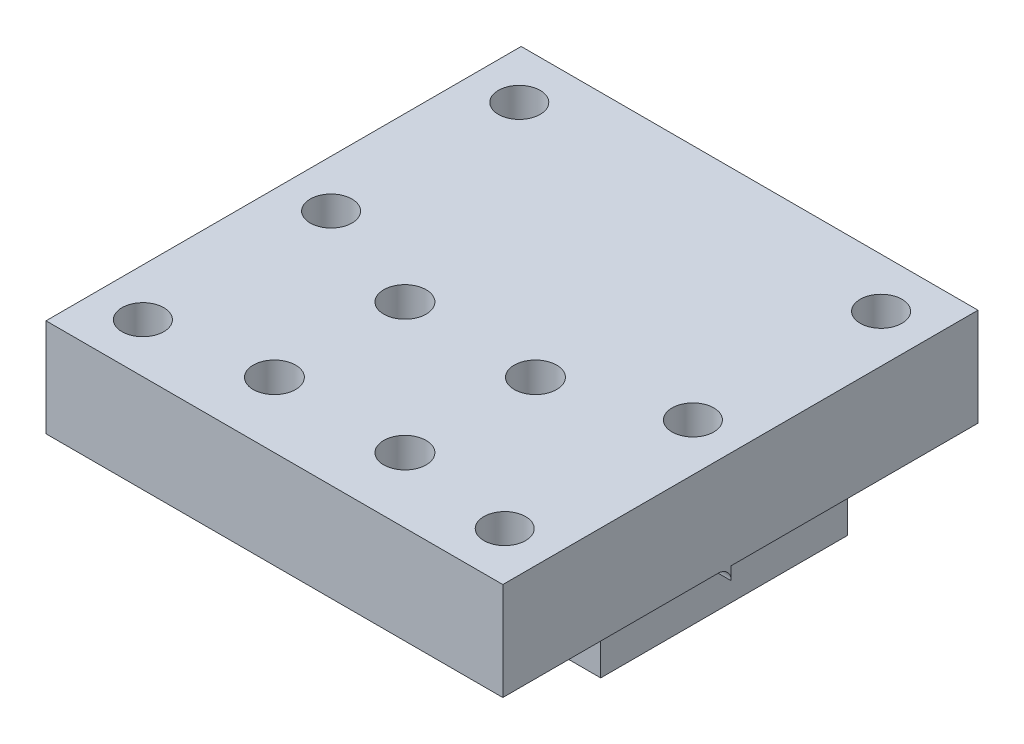
SolidWorks part; units mm, degrees
ref_plane "Front Plane" through (0, 0, 0) normal (0, 0, 1) x (1, 0, 0)
ref_plane "Top Plane" through (0, 0, 0) normal (0, 1, 0) x (1, 0, 0)
ref_plane "Right Plane" through (0, 0, 0) normal (1, 0, 0) x (0, 0, -1)
sketch "Sketch1" plane through (0, 0, 0) normal (0, 1, 0) x (1, 0, 0)
  line L1 (-35, 20) -> (35, 20)
  line L2 (-35, 20) -> (-35, -20)
  line L3 (-35, -20) -> (35, -20)
  line L4 (35, 20) -> (35, -20)
  line L5 (-35, 20) -> (35, -20) construction
  line L6 (-35, -20) -> (35, 20) construction
  line L7 (-10, 10) -> (10, 10) construction
  line L8 (-10, 10) -> (-10, -10) construction
  line L9 (-10, -10) -> (10, -10) construction
  line L10 (10, 10) -> (10, -10) construction
  line L11 (-10, 10) -> (10, -10) construction
  line L12 (-10, -10) -> (10, 10) construction
  circle A0 centre (10, 10) radius 1.6
  circle A1 centre (10, -10) radius 1.6
  circle A2 centre (-10, -10) radius 1.6
  circle A3 centre (-10, 10) radius 1.6
  point P0 (0, 0)
  point P5 (0, 0)
  point P12 (-10, 9.9651)
  point P21 (0, 0)
  dimension "D3" = 3.2
  dimension "D1" = 20
  dimension "D2" = 20
  dimension "D5" = 70
  dimension "D6" = 40
  dimension "D4" = 4
extrude "Boss-Extrude1" add sketch "Sketch1" along normal blind 15
sketch "Sketch2" plane through (0, 15, 0) normal (0, 1, 0) x (1, 0, 0)
  circle A0 centre (10, 10) radius 3.25
  circle A1 centre (10, -10) radius 3.25
  circle A2 centre (-10, -10) radius 3.25
  circle A3 centre (-10, 10) radius 3.25
  point P3 (-10, 10)
  point P12 (0, 0)
  dimension "D1" = 6.5
  dimension "D2" = 4
extrude "Cut-Extrude1" cut sketch "Sketch2" against normal offset from surface (5 mm away) 10 up to face at (0, 0, 0)
sketch "Sketch3" plane through (0, 15, 0) normal (0, 1, 0) x (1, 0, 0)
  line L0 (35, 20) -> (-35, 20) construction
  line L5 (-35, 15) -> (35, 15)
  line L6 (-35, 15) -> (-35, 52.813)
  line L7 (-35, 52.813) -> (35, 52.813)
  line L8 (35, 15) -> (35, 52.813)
  line L9 (35, -20) -> (35, 20) construction
  line L10 (-35, 20) -> (-35, -20) construction
  point P4 (0, 0)
  dimension "D1" = 37.813
  dimension "D2" = 5
extrude "Boss-Extrude2" add sketch "Sketch3" against normal blind 39.8969
fillet "Fillet1" radius 2 1 edges at (0, 0, -15)
sketch "Sketch4" plane through (0, 15, 0) normal (0, 1, 0) x (1, 0, 0)
  line L0 (-35, 52.813) -> (35, -20) construction
  line L1 (-35, -20) -> (35, -20) construction
  line L2 (35, -20) -> (35, 52.813) construction
  line L3 (-35, -20) -> (35, 52.813) construction
  line L4 (0, 16.4065) -> (0, 35.737) construction
  line L5 (0, 16.4065) -> (23.279, 16.4065) construction
  line L6 (27.7218, 45.2423) -> (27.7218, -12.4293) construction
  circle A0 centre (27.7218, 45.2423) radius 3.2
  circle A1 centre (-27.7218, 45.2423) radius 3.2
  circle A2 centre (-27.7218, -12.4293) radius 3.2
  circle A3 centre (27.7218, -12.4293) radius 3.2
  circle A4 centre (27.7218, 16.4065) radius 3.2
  circle A5 centre (-27.7218, 16.4065) radius 3.2
  point P14 (0, 16.4065)
  dimension "D1" = 6.4
  dimension "D2" = 40
extrude "Cut-Extrude2" cut sketch "Sketch4" against normal blind 8
sketch "Sketch5" plane through (0, -24.8969, 0) normal (0, -1, 0) x (1, 0, 0)
  line L0 (-35, -52.813) -> (-35, -15) construction
  line L1 (-35, -30.9065) -> (35, -30.9065) construction
  line L2 (-35, -30.9065) -> (-35, -36.9065) construction
  line L3 (-35, -36.9065) -> (35, -36.9065) construction
  line L4 (35, -30.9065) -> (35, -36.9065) construction
  line L5 (35, -15) -> (35, -52.813) construction
  line L6 (-35, -33.9065) -> (35, -33.9065) construction
  line L7 (0, -22.9065) -> (0, -44.9065) construction
  circle A0 centre (0, -22.9065) radius 3.2
  circle A1 centre (0, -44.9065) radius 3.2
  circle A2 centre (-22, -22.9065) radius 3.2
  circle A3 centre (-22, -44.9065) radius 3.2
  point P10 (35, -33.9065)
  point P11 (0, -33.9065)
  point P18 (0, -44.4581)
  dimension "D2" = 8
  dimension "D3" = 6.4
  dimension "D5" = 22
  dimension "D1" = 6
  dimension "D4" = 11
extrude "Cut-Extrude3" cut sketch "Sketch5" against normal blind 10
sketch "Sketch7" plane through (0, -24.8969, 0) normal (0, -1, 0) x (1, 0, 0)
  line L0 (35, -52.813) -> (-35, -52.813) construction
  line L1 (35, -15) -> (15, -15)
  line L2 (35, -15) -> (35, -52.813)
  line L3 (35, -52.813) -> (15, -52.813)
  line L4 (15, -15) -> (15, -52.813)
  dimension "D1" = 20
extrude "Cut-Extrude4" cut sketch "Sketch7" against normal up to surface (24.8969 mm away) up to face at (0, 0, 3.5)
fillet "Fillet2" radius 2 1 edges at (15, 0, -33.9065)
